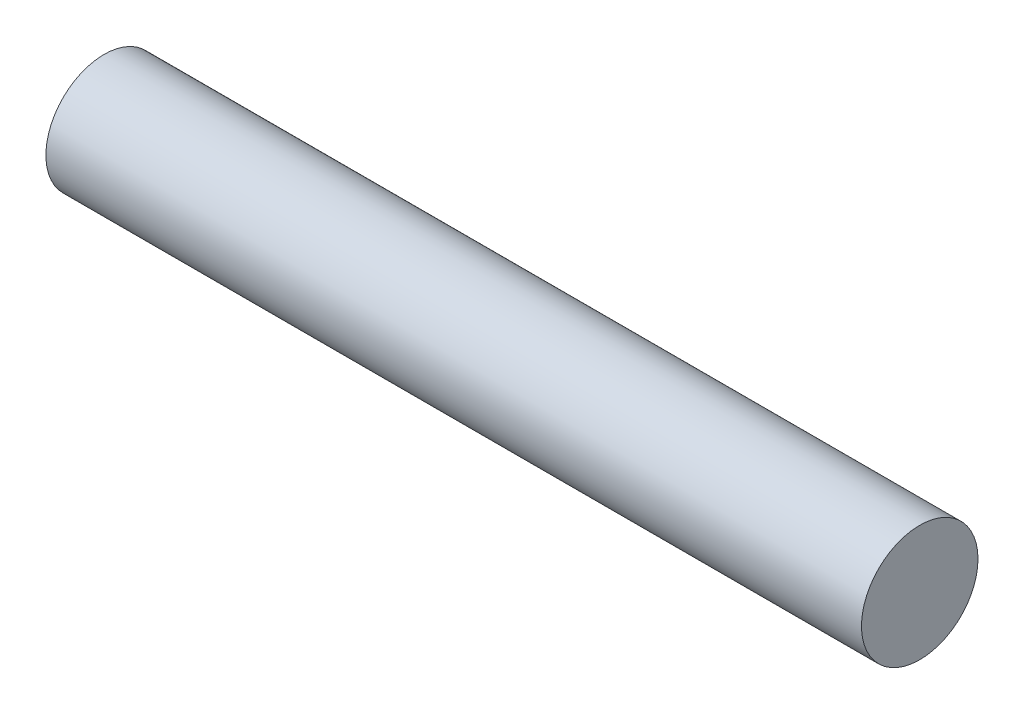
SolidWorks part; units mm, degrees
ref_plane "Front Plane" through (0, 0, 0) normal (0, 0, 1) x (1, 0, 0)
ref_plane "Top Plane" through (0, 0, 0) normal (0, 1, 0) x (1, 0, 0)
ref_plane "Right Plane" through (0, 0, 0) normal (1, 0, 0) x (0, 0, -1)
sketch "Sketch1" plane through (0, 0, 0) normal (1, 0, 0) x (0, 0, -1)
  circle A0 centre (0, 0) radius 1
  dimension "D1" = 2
extrude "Boss-Extrude1" add sketch "Sketch1" along normal blind 14
ref_plane "Plane1" through (7, 0, 0) normal (1, 0, 0) x (0, 0, -1)
